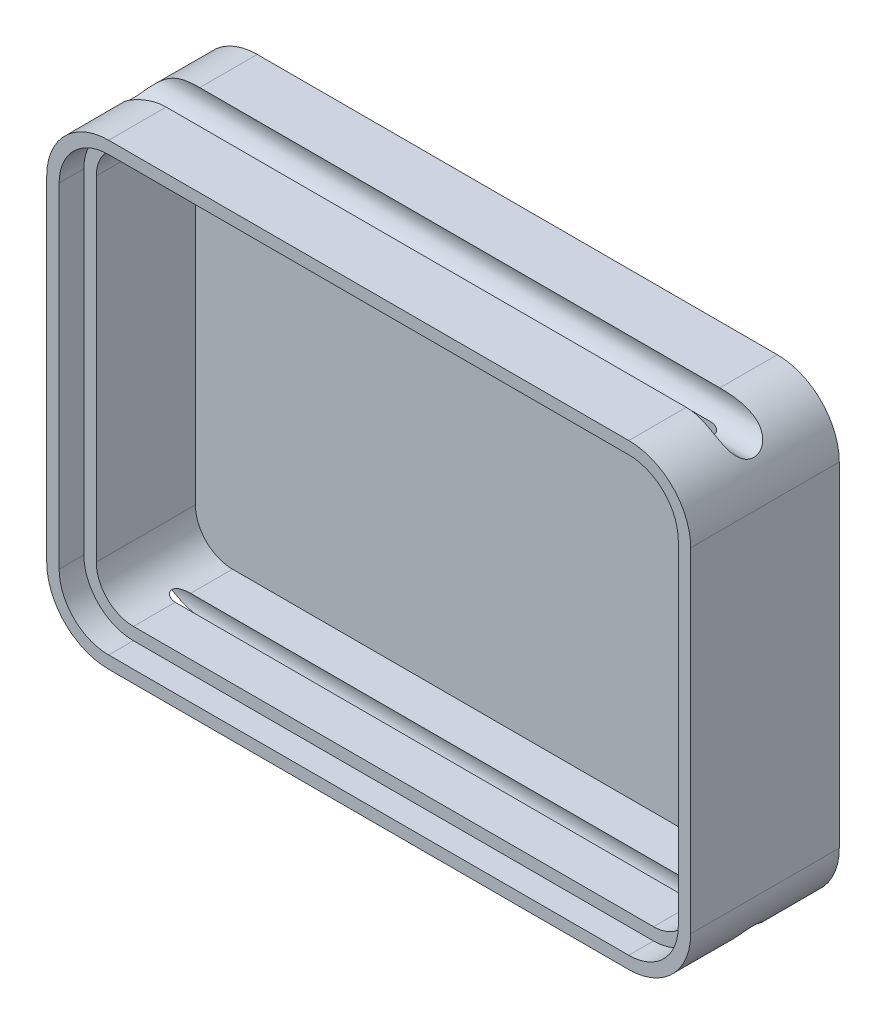
SolidWorks part; units mm, degrees
ref_plane "Plan de face" through (0, 0, 0) normal (0, 0, 1) x (1, 0, 0)
ref_plane "Plan de dessus" through (0, 0, 0) normal (0, 1, 0) x (1, 0, 0)
ref_plane "Plan de droite" through (0, 0, 0) normal (1, 0, 0) x (0, 0, -1)
sketch "Esquisse1" plane through (0, 0, 0) normal (0, 0, 1) x (1, 0, 0)
  line L1 (5, 0) -> (47, 0)
  line L2 (0, 5) -> (0, 32)
  line L3 (5, 37) -> (47, 37)
  line L4 (52, 5) -> (52, 32)
  arc A0 (47, 37) -> (52, 32) centre (47, 32) cw
  arc A1 (47, 0) -> (52, 5) centre (47, 5) ccw
  arc A2 (5, 0) -> (0, 5) centre (5, 5) cw
  arc A3 (0, 32) -> (5, 37) centre (5, 32) cw
  point P9 (52, 0)
  point P12 (0, 0)
  point P15 (0, 37)
  dimension "D3" = 5
  dimension "D1" = 37
  dimension "D2" = 52
extrude "Boss.-Extru.1" add sketch "Esquisse1" along normal blind 12
shell "Coque5" thickness 2
sketch "Esquisse3" plane through (0, 0, 12) normal (0, 0, 1) x (1, 0, 0)
  line L8 (47, 36) -> (5, 36)
  line L9 (1, 32) -> (1, 5)
  line L10 (5, 1) -> (47, 1)
  line L11 (51, 5) -> (51, 32)
  line L12 (47, 36) -> (5, 36)
  line L13 (1, 32) -> (1, 5)
  line L14 (5, 1) -> (47, 1)
  line L15 (51, 5) -> (51, 32)
  arc A8 (51, 32) -> (47, 36) centre (47, 32) ccw
  arc A9 (5, 36) -> (1, 32) centre (5, 32) ccw
  arc A10 (1, 5) -> (5, 1) centre (5, 5) ccw
  arc A11 (47, 1) -> (51, 5) centre (47, 5) ccw
  arc A12 (51, 32) -> (47, 36) centre (47, 32) ccw
  arc A13 (5, 36) -> (1, 32) centre (5, 32) ccw
  arc A14 (1, 5) -> (5, 1) centre (5, 5) ccw
  arc A15 (47, 1) -> (51, 5) centre (47, 5) ccw
  dimension "D1" = 1
extrude "Enlèv. mat.-Extru.1" cut sketch "Esquisse3" against normal blind 2 contours A12 L12 A13 L13 A14 L14 A15 L15
sketch "Esquisse4" [suppressed] plane through (0, 0, 2) normal (0, 0, 1) x (1, 0, 0)
  line L0 (29.8171, 28.7082) -> (29.8171, 6.2082)
  line L1 (28.8171, 27.7082) -> (3.8171, 27.7082)
  line L2 (28.8171, 27.7082) -> (28.8171, 7.2082)
  line L3 (28.8171, 7.2082) -> (3.8171, 7.2082)
  line L4 (3.8171, 27.7082) -> (3.8171, 7.2082)
  line L5 (29.8171, 6.2082) -> (2.8171, 6.2082)
  line L6 (2.8171, 28.7082) -> (2.8171, 6.2082)
  line L7 (29.8171, 28.7082) -> (2.8171, 28.7082)
  dimension "D1" = 25
  dimension "D2" = 20.5
  dimension "D3" = 1
extrude "Boss.-Extru.3" [suppressed] add sketch "Esquisse4" along normal blind 5
sketch "Esquisse7" plane through (52, 0, 0) normal (1, 0, 0) x (0, 0, -1)
  circle A0 centre (-6, 36.365) radius 1.5
  dimension "D1" = 3
extrude "Enlèv. mat.-Extru.2" cut sketch "Esquisse7" against normal through all
sketch "Esquisse8" plane through (52, 0, 0) normal (1, 0, 0) x (0, 0, -1)
  circle A0 centre (-6, 0.635) radius 1.5
  dimension "D1" = 3
extrude "Enlèv. mat.-Extru.3" cut sketch "Esquisse8" against normal through all
sketch "Esquisse9" plane through (0, 0, 0) normal (-1, 0, 0) x (0, 0, 1)
  line L4 (6.55, 22.7082) -> (3.55, 22.7082)
  line L5 (6.55, 22.7082) -> (6.55, 12.7082)
  line L6 (6.55, 12.7082) -> (3.55, 12.7082)
  line L7 (3.55, 22.7082) -> (3.55, 12.7082)
  dimension "D2" = 10
  dimension "D3" = 3
extrude "Enlèv. mat.-Extru.4" [suppressed] cut sketch "Esquisse9" against normal up to vertex and the other way through all
